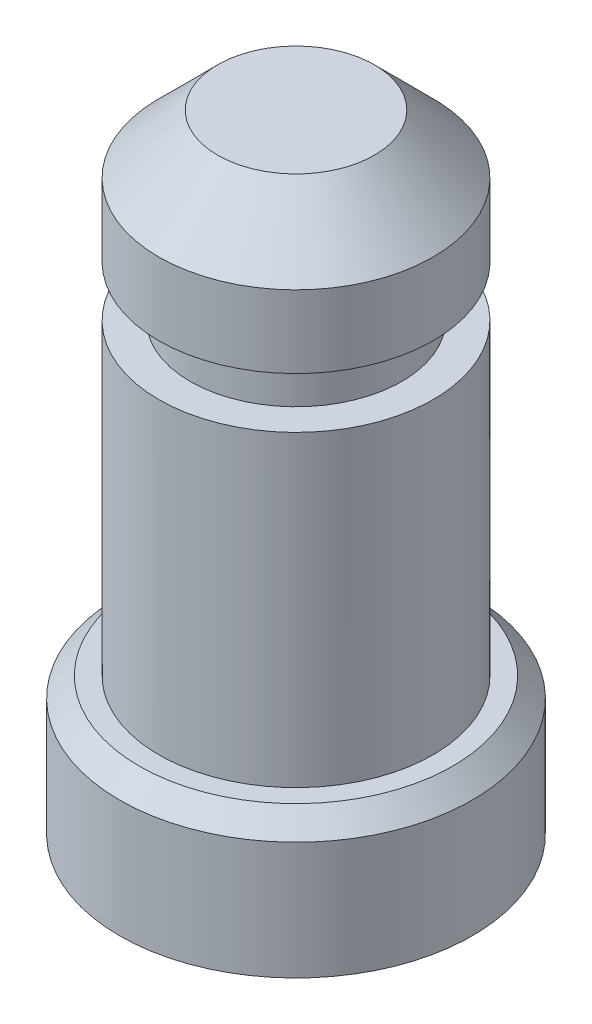
SolidWorks part; units mm, degrees
ref_plane "前视基准面" through (0, 0, 0) normal (0, 0, 1) x (1, 0, 0)
ref_plane "上视基准面" through (0, 0, 0) normal (0, 1, 0) x (1, 0, 0)
ref_plane "右视基准面" through (0, 0, 0) normal (1, 0, 0) x (0, 0, -1)
sketch "草图1" plane through (0, 0, 0) normal (0, 1, 0) x (1, 0, 0)
  circle A0 centre (0, 0) radius 3.5
  dimension "D1" = 7
extrude "凸台-拉伸1" add sketch "草图1" along normal mid plane 16
sketch "草图2" plane through (0, 0, 0) normal (0, 0, 1) x (1, 0, 0)
  line L0 (3.5, -8) -> (4.5, -8)
  line L1 (4.5, -8) -> (4.5, -4.5)
  line L2 (4.5, -4.5) -> (3.5, -4.5)
  line L3 (3.5, -8) -> (3.5, 8) construction
  line L4 (3.5, -4.5) -> (3.5, -8)
  dimension "D1" = 1
  dimension "D2" = 3.5
revolve "旋转1" add sketch "草图2" angle 360 about axis through (0, 8, 0) along (0, -1, 0)
hole_wizard "M4 螺纹孔1" positions "草图5" profile "草图4" tap size "M4" standard "GB"
sketch "草图5" plane through (0, -8, 0) normal (0, -1, 0) x (-1, 0, 0)
  point P0 (0, 0)
sketch "草图4" plane through (0, -8, 0) normal (1, 0, 0) x (0, 0, -1)
  line L0 (0, 0) -> (0, 11.0914)
  line L1 (0, 11.0914) -> (1.65, 10.1)
  line L2 (1.65, 10.1) -> (1.65, 0)
  line L5 (1.65, 0) -> (0, 0)
  line L10 (0, 11.0914) -> (-1.65, 10.1) construction
  line L11 (0, -6.35) -> (0, 107.95) construction
  dimension "螺纹孔钻头直径" = 3.3
  dimension "螺纹孔钻头深度" = 10.1
  dimension "导头角度" = 118
cosmetic thread "孔螺蚊线1" parameters "D1"=8, "D2"=4
chamfer "倒角1" distance 1.5 angle 45 1 edges at (0, 8, 3.5)
sketch "草图6" plane through (0, 0, 0) normal (0, 0, 1) x (1, 0, 0)
  line L0 (3.5, 4) -> (-3.5, 4) construction
  line L1 (3.5, -4.5) -> (3.5, 6.5) construction
  line L2 (-3.5, 6.5) -> (-3.5, -4.5) construction
  line L3 (2, 8) -> (-2, 8) construction
  line L4 (3.5, 3.35) -> (3.5, 4.65)
  line L5 (3.5, 4.65) -> (2.7, 4.65)
  line L6 (2.7, 4.65) -> (2.7, 3.35)
  line L7 (2.7, 3.35) -> (3.5, 3.35)
  dimension "D1" = 4
  dimension "D2" = 0.8
  dimension "D3" = 1.3
revolve "切除-旋转1" cut sketch "草图6" angle 360 about axis through (0, 8, 0) along (0, -1, 0)
chamfer "倒角2" distance 0.5 angle 45 1 edges at (0, -4.5, 4.5)
